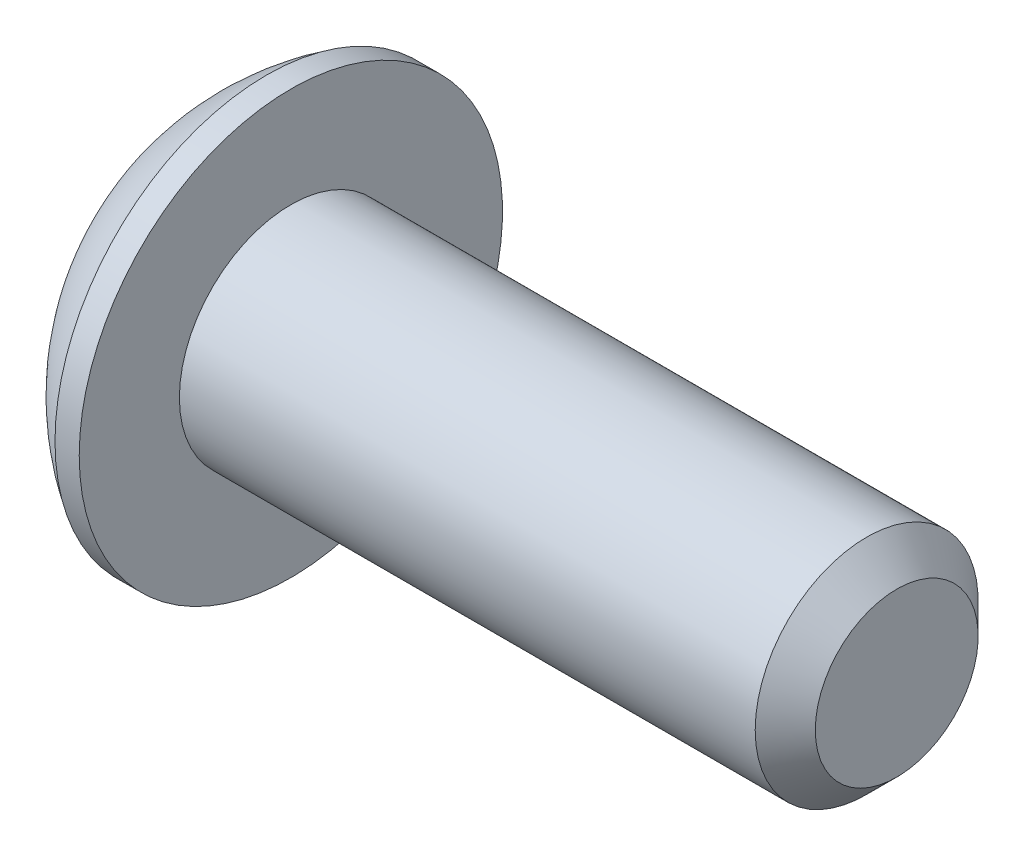
SolidWorks part; units mm, degrees
other "Defeature"
material "Alloy Steel"
ref_plane "Plane1" through (0, 0, 0) normal (0, 0, 1) x (1, 0, 0)
ref_plane "Plane2" through (0, 0, 0) normal (0, 1, 0) x (1, 0, 0)
ref_plane "Plane3" through (0, 0, 0) normal (1, 0, 0) x (0, 0, -1)
sketch "BodySke" plane through (0, 0, 0) normal (0, 0, 1) x (1, 0, 0)
  line L0 (11.3792, 0) -> (11.3792, 1.2802)
  line L1 (10.9068, 1.7526) -> (1.8542, 1.7526)
  line L2 (1.8542, 1.7526) -> (1.8542, 3.3274)
  line L3 (1.8542, 3.3274) -> (1.4732, 3.3274)
  line L4 (0, 0) -> (101.6, 0) construction
  line L5 (1.8542, -3.3274) -> (1.4732, -3.3274) construction
  line L6 (55.6768, -1.7526) -> (1.8542, -1.7526) construction
  line L7 (11.3792, 0) -> (0, 0)
  line L8 (0, 1.6637) -> (0, -1.6637) construction
  line L9 (0, 0) -> (0, 1.6637)
  line L10 (11.3792, 1.2802) -> (10.9068, 1.7526)
  line L11 (11.3792, -1.2802) -> (10.9068, -1.7526) construction
  line L12 (2.6467, 9.525) -> (2.6467, -1.7526) construction
  line L13 (1.8542, 9.525) -> (1.8542, -1.7526) construction
  arc A1 (0, 1.6637) -> (1.4732, 3.3274) centre (3.5549, 0) cw
  dimension "Diameter" = 3.5052
  dimension "Length" = 9.525
  dimension "Head_dia" = 6.6548
  dimension "D1" = 3.3274
  dimension "Head_ht" = 1.8542
  dimension "Head_side_ht" = 0.381
  dimension "Minor_dia" = 2.5603
  dimension "Body_ch_ang" = 45
  dimension "Advance" = 0.7925
  dimension "Thread_nom" = 9.525
revolve "BaseBody" add sketch "BodySke" angle 360 about L4
cosmetic thread "ThreadCosmetic" parameters "Thread_length"=8.7325, "Thread_minor"=2.5603
sketch "Sketch2" plane through (0, 0, 0) normal (0, 0, 1) x (1, 0, 0)
  line L0 (0, 0.9906) -> (1.1176, 0.9906)
  line L1 (1.1176, 0.9906) -> (1.6895, 0)
  line L3 (1.6895, 0) -> (0, 0)
  line L4 (0, 0) -> (0, 0.9906)
  line L5 (0, -0.9906) -> (1.1176, -0.9906) construction
  line L6 (0, 0) -> (47.625, 0) construction
  dimension "D2" = 60
  dimension "PreBroach_depth" = 1.1176
  dimension "PreBroach_dia" = 1.9812
revolve "PreBroach" cut sketch "Sketch2" angle 360 about L6
sketch "Sketch3" plane through (0, 0, 0) normal (1, 0, 0) x (0, 0, -1)
  line L0 (-0.9906, -0.5719) -> (-0.9906, 0.5719)
  line L1 (-0.9906, 0.5719) -> (0, 1.1438)
  line L2 (0, 1.1438) -> (0.9906, 0.5719)
  line L3 (0.9906, 0.5719) -> (0.9906, -0.5719)
  line L4 (0.9906, -0.5719) -> (0, -1.1438)
  line L5 (0, -1.1438) -> (-0.9906, -0.5719)
  dimension "Hex_size" = 1.9812
  dimension "D3" = 1.9812
  dimension "D1" = 0.9906
  dimension "D2" = 0.9906
extrude "Hex" cut sketch "Sketch3" along normal blind 1.1176
sketch "Sketch4" plane through (0, 9.525, 0) normal (1, 0, 0) x (0, 0, -1)
  line L0 (0, -9.525) -> (1.2446, -9.525)
  line L1 (0, -9.525) -> (6.1484, -5.9752) construction
  line L2 (0, -9.525) -> (0.6223, -8.4471)
  line L3 (1.0085, -9.2654) -> (1.19, -9.1606)
  line L4 (0.7291, -8.7814) -> (0.9106, -8.6766)
  arc A0 (1.0085, -9.2654) -> (0.7291, -8.7814) centre (0, -9.525) ccw
  arc A1 (1.2446, -9.525) -> (1.19, -9.1606) centre (0, -9.525) ccw
  arc A2 (0.6223, -8.4471) -> (0.9106, -8.6766) centre (0, -9.525) cw
  dimension "Spline_n_dim" = 2.0828
  dimension "Spline_m_dim" = 2.4892
  dimension "D1" = 30
  dimension "D2" = 60
  dimension "Spline_p_dim" = 0.5588
  dimension "D3" = 0.2794
extrude "Spline" [suppressed] cut sketch "Sketch4" along normal blind 1.1176
pattern_circular "CirPattern1" [suppressed] count 6 every 60 about axis through (0, 0, 0) along (1, 0, 0)
sketch "ThdSchSke" plane through (0, 0, 0) normal (0, 0, 1) x (1, 0, 0)
  line L0 (2.6467, -1.2802) -> (2.3159, -1.7526)
  line L1 (2.6467, -1.2802) -> (2.9775, -1.7526)
  line L2 (2.9775, -1.7526) -> (2.9775, -2.1908)
  line L3 (-3.175, 0) -> (5.1513, 0) construction
  line L5 (2.9775, -2.1908) -> (2.3159, -2.1908)
  line L6 (2.3159, -2.1908) -> (2.3159, -1.7526)
  dimension "Diameter" = 3.5052
  dimension "Thread_minor" = 2.5603
  dimension "SideAngle" = 55
  dimension "VeeAngle" = 70
  dimension "Overcut" = 4.3815
  dimension "Start" = 2.6467
revolve "ThreadSchematic" [suppressed] cut sketch "ThdSchSke" angle 360 about L3
pattern_linear "ThdSchPat" [suppressed]
equation "\"D1@BodySke\" = \"Head_dia@BodySke\" * .5"
equation "\"Thread_minor@ThreadCosmetic\" = \"Minor_dia@BodySke\""
equation "\"D1@Sketch3\" = \"Hex_size@Sketch3\" / 2"
equation "\"D2@Sketch3\" = \"D1@Sketch3\""
equation "\"D3@Sketch3\" = \"Hex_size@Sketch3\""
equation "\"D3@Sketch4\" = \"Spline_p_dim@Sketch4\" / 2"
equation "\"D1@Sketch4\" = \"D2@Sketch4\" / 2"
equation "\"Thread_length@ThreadCosmetic\" = ((sgn( (\"Length@BodySke\" - \"Advance@BodySke\" ) - \"Thread_nom@BodySke\" )-1)*( (\"Length@BodySke\" - \"Advance@BodySke\" ) - \"Thread_nom@BodySke\" ))/-2+ \"Thread_nom@BodySke\""
equation "\"Thread_minor@ThdSchSke\" = \"Minor_dia@BodySke\""
equation "\"Diameter@ThdSchSke\" = \"Diameter@BodySke\""
equation "\"Overcut@ThdSchSke\" = \"Diameter@BodySke\" * 1.25"
equation "\"Start@ThdSchSke\" = \"Head_ht@BodySke\" + \"Length@BodySke\" - \"Thread_length@ThreadCosmetic\"  '---Non-countersunk---"
equation "\"Num_threads@ThdSchPat\" = int( \"Thread_length@ThreadCosmetic\" / \"Advance@BodySke\" + 0.999 )  + 1"
equation "\"Advance@ThdSchPat\" = \"Thread_length@ThreadCosmetic\" /  (\"Num_threads@ThdSchPat\" - 1) 'relax it"
equation "\"Num_threads@ThdSchPat\" = \"Num_threads@ThdSchPat\" - sgn( \"Num_threads@ThdSchPat\" - 1) '---chamfered tips only---"
